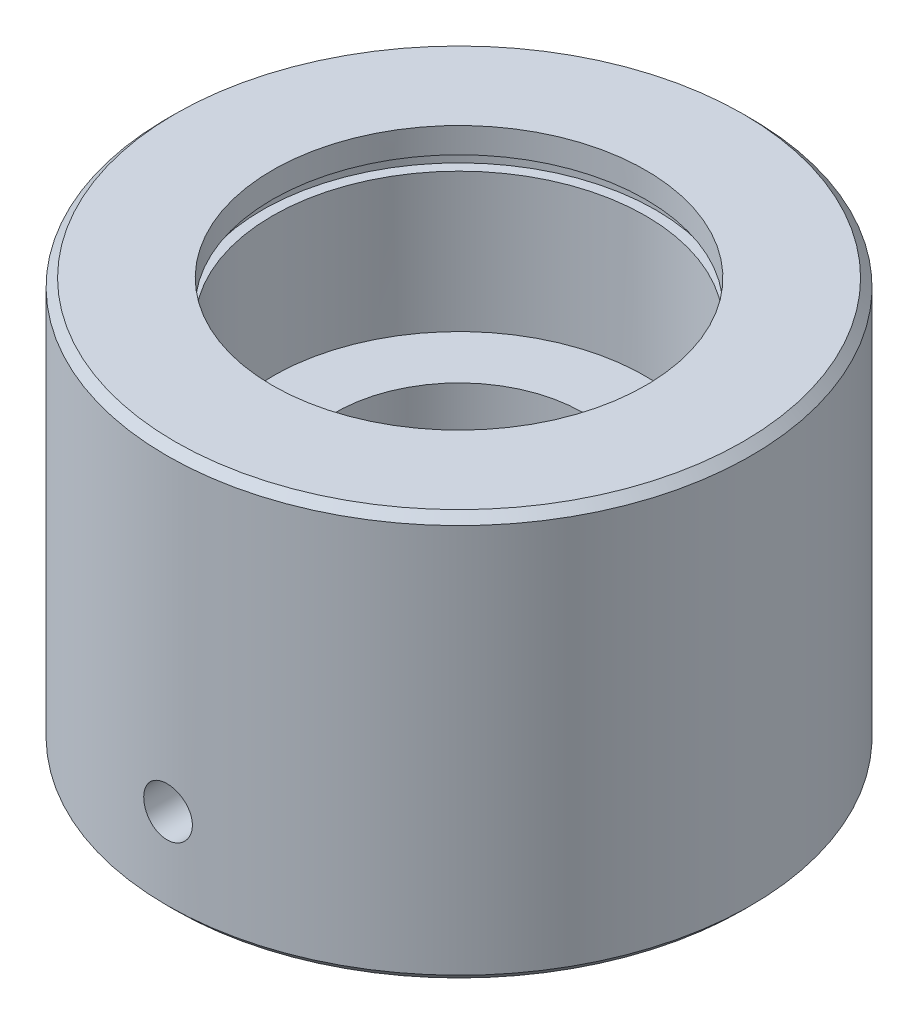
SolidWorks part; units mm, degrees
material "AISI 1045 Steel, cold drawn"
ref_plane "Front Plane" through (0, 0, 0) normal (0, 0, 1) x (1, 0, 0)
ref_plane "Top Plane" through (0, 0, 0) normal (0, 1, 0) x (1, 0, 0)
ref_plane "Right Plane" through (0, 0, 0) normal (1, 0, 0) x (0, 0, -1)
sketch "Sketch1" plane through (0, 0, 0) normal (0, 1, 0) x (1, 0, 0)
  circle A0 centre (0, 0) radius 36
  dimension "D1" = 72
extrude "Boss-Extrude1" add sketch "Sketch1" along normal blind 50
sketch "Sketch2" plane through (0, 50, 0) normal (0, 1, 0) x (1, 0, 0)
  circle A0 centre (0, 0) radius 23
  dimension "D1" = 46
extrude "Cut-Extrude1" cut sketch "Sketch2" against normal blind 22
sketch "Sketch3" plane through (0, 0, 0) normal (0, -1, 0) x (1, 0, 0)
  circle A0 centre (0, 0) radius 14
  dimension "D1" = 28
extrude "Cut-Extrude2" cut sketch "Sketch3" against normal blind 22
sketch "Sketch4" plane through (0, 28, 0) normal (0, 1, 0) x (1, 0, 0)
  circle A0 centre (0, 0) radius 15.25
  dimension "D1" = 30.5
extrude "Cut-Extrude3" cut sketch "Sketch4" against normal blind 6
sketch "Sketch5" plane through (0, 0, 0) normal (0, 0, 1) x (1, 0, 0)
  line L0 (0, 0) -> (0, 55.0563) construction
  line L1 (36, 50) -> (-36, 50) construction
  line L2 (23, 46.875) -> (24.25, 46.875)
  line L3 (23, 46.875) -> (23, 45.125)
  line L4 (23, 45.125) -> (24.25, 45.125)
  line L5 (24.25, 46.875) -> (24.25, 45.125)
  dimension "D1" = 1.75
  dimension "D2" = 3.125
  dimension "D3" = 24.25
  dimension "D4" = 23
revolve "Cut-Revolve1" cut sketch "Sketch5" angle 360 about L0
sketch "Sketch6" plane through (0, 0, 0) normal (0, 0, 1) x (1, 0, 0)
  line L0 (0, 0) -> (0, 50) construction
  line L1 (36, 50) -> (-36, 50) construction
  line L2 (-36, 0) -> (36, 0) construction
  circle A0 centre (0, 11) radius 3
  dimension "D1" = 6
  dimension "D2" = 11
extrude "Cut-Extrude4" cut sketch "Sketch6" against normal through all both and the other way through all
chamfer "Chamfer1" distance 1 angle 45 2 edges at (0, 0, 36) (0, 50, 36)
